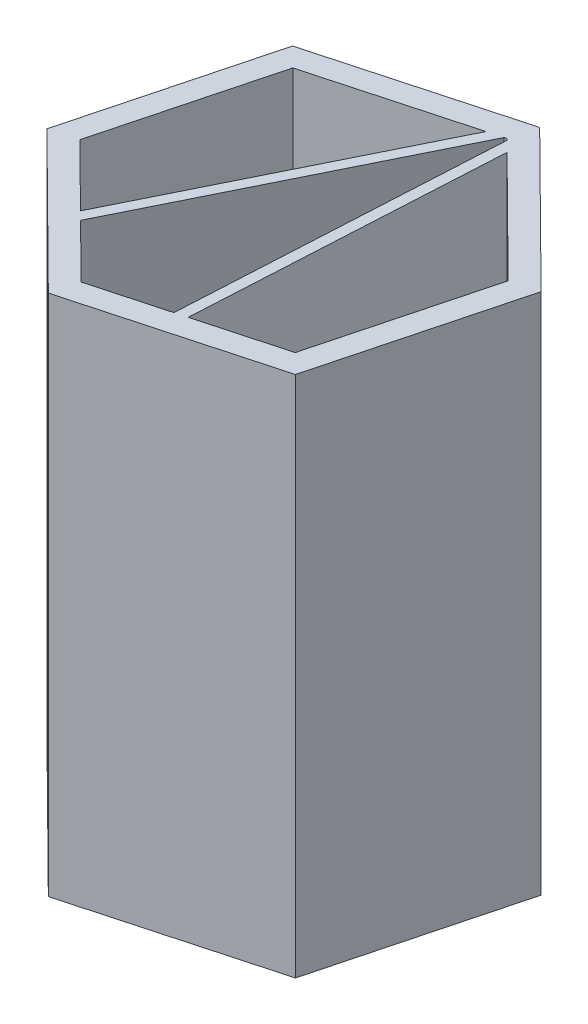
SolidWorks part; units mm, degrees
ref_plane "Front Plane" through (0, 0, 0) normal (0, 0, 1) x (1, 0, 0)
ref_plane "Top Plane" through (0, 0, 0) normal (0, 1, 0) x (1, 0, 0)
ref_plane "Right Plane" through (0, 0, 0) normal (1, 0, 0) x (0, 0, -1)
sketch "Sketch1" plane through (0, 0, 0) normal (0, 1, 0) x (1, 0, 0)
  line L1 (12.3088, -12.1857) -> (16.7076, 4.5669)
  line L2 (16.7076, 4.5669) -> (4.3987, 16.7526)
  line L3 (4.3987, 16.7526) -> (-12.3088, 12.1857)
  line L4 (-12.3088, 12.1857) -> (-16.7076, -4.5669)
  line L5 (-16.7076, -4.5669) -> (-4.3987, -16.7526)
  line L6 (-4.3987, -16.7526) -> (12.3088, -12.1857)
  line L7 (-3.8122, -14.519) -> (10.6677, -10.561)
  line L8 (10.6677, -10.561) -> (14.4799, 3.958)
  line L9 (14.4799, 3.958) -> (3.8122, 14.519)
  line L10 (3.8122, 14.519) -> (-10.6677, 10.561)
  line L11 (-10.6677, 10.561) -> (-14.4799, -3.958)
  line L12 (-14.4799, -3.958) -> (-3.8122, -14.519)
  circle A0 centre (0, 0) radius 15 construction
  circle A1 centre (0, 0) radius 13 construction
  dimension "D1" = 30
  dimension "D2" = 2
extrude "Boss-Extrude1" add sketch "Sketch1" along normal blind 45
sketch "Sketch2" plane through (0, 45, 0) normal (0, 1, 0) x (1, 0, 0)
  line L0 (-9.1461, -9.2385) -> (2.3961, 14.1319)
  line L1 (-14.4799, -3.958) -> (-3.8122, -14.519) construction
  line L2 (3.8122, 14.519) -> (-10.6677, 10.561) construction
  line L3 (2.3961, 14.1319) -> (3.6193, 14.4662)
  line L4 (3.6193, 14.4662) -> (-8.4354, -9.942)
  line L5 (-8.4354, -9.942) -> (-9.1461, -9.2385)
  line L6 (3.4277, -12.54) -> (4.8556, 13.4861)
  line L7 (-3.8122, -14.519) -> (10.6677, -10.561) construction
  line L8 (14.4799, 3.958) -> (3.8122, 14.519) construction
  line L9 (4.8556, 13.4861) -> (3.9544, 14.3782)
  line L10 (3.9544, 14.3782) -> (2.4631, -12.8036)
  line L11 (2.4631, -12.8036) -> (3.4277, -12.54)
  dimension "D1" = 0.2
  dimension "D2" = 0.2
  dimension "D3" = 1
  dimension "D4" = 1
extrude "Boss-Extrude2" add sketch "Sketch2" against normal blind 45
